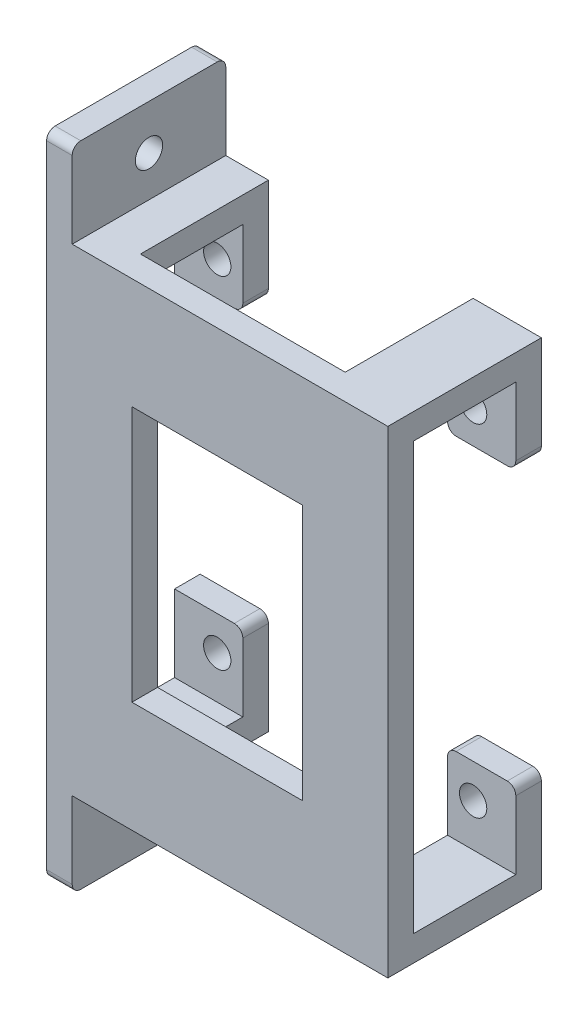
SolidWorks part; units mm, degrees
ref_plane "前视基准面" through (0, 0, 0) normal (0, 0, 1) x (1, 0, 0)
ref_plane "上视基准面" through (0, 0, 0) normal (0, 1, 0) x (1, 0, 0)
ref_plane "右视基准面" through (0, 0, 0) normal (1, 0, 0) x (0, 0, -1)
sketch "草图1" plane through (0, 0, 0) normal (0, 0, 1) x (1, 0, 0)
  line L1 (-15, -20) -> (15, -20) construction
  line L2 (-15, -20) -> (-15, 20) construction
  line L3 (-15, 20) -> (15, 20) construction
  line L4 (15, -20) -> (15, 20) construction
  line L5 (-15, -20) -> (15, 20) construction
  line L6 (-15, 20) -> (15, -20) construction
  line L7 (-20, -25) -> (20, -25)
  line L8 (-20, -25) -> (-20, 25)
  line L9 (-20, 25) -> (20, 25)
  line L10 (20, -25) -> (20, 25)
  line L11 (-20, -25) -> (20, 25) construction
  line L12 (-20, 25) -> (20, -25) construction
  circle A0 centre (-15, 20) radius 1.6
  circle A1 centre (15, 20) radius 1.6
  circle A2 centre (15, -20) radius 1.6
  circle A3 centre (-15, -20) radius 1.6
  point P0 (0, 0)
  point P5 (0, 0)
  dimension "D5" = 3.2
  dimension "D1" = 40
  dimension "D2" = 30
  dimension "D3" = 5
  dimension "D4" = 5
extrude "凸台-拉伸1" add sketch "草图1" along normal blind 3
sketch "草图2" plane through (0, 0, 0) normal (0, 0, -1) x (-1, 0, 0)
  line L1 (-20, 25) -> (-12, 25)
  line L2 (-20, 25) -> (-20, 28)
  line L3 (-20, 28) -> (-12, 28)
  line L4 (-12, 25) -> (-12, 28)
  line L5 (20, 25) -> (12, 25)
  line L6 (20, 25) -> (20, 28)
  line L7 (20, 28) -> (12, 28)
  line L8 (12, 25) -> (12, 28)
  line L9 (-20, -25) -> (-12, -25)
  line L10 (-20, -25) -> (-20, -28)
  line L11 (-20, -28) -> (-12, -28)
  line L12 (-12, -25) -> (-12, -28)
  line L13 (20, -25) -> (12, -25)
  line L14 (20, -25) -> (20, -28)
  line L15 (20, -28) -> (12, -28)
  line L16 (12, -25) -> (12, -28)
  dimension "D1" = 3
  dimension "D2" = 3
  dimension "D3" = 8
extrude "凸台-拉伸2" add sketch "草图2" against normal blind 15
sketch "草图3" plane through (0, 0, 15) normal (0, 0, 1) x (1, 0, 0)
  line L1 (-20, 28) -> (20, 28)
  line L2 (-20, 28) -> (-20, -28)
  line L3 (-20, -28) -> (20, -28)
  line L4 (20, 28) -> (20, -28)
  line L5 (20, -28) -> (12, -28) construction
extrude "凸台-拉伸3" add sketch "草图3" along normal blind 3
sketch "草图4" plane through (0, 0, 0) normal (0, 0, -1) x (-1, 0, 0)
  line L0 (20, 28) -> (20, -28) construction
  line L1 (-20, -16) -> (20, -16)
  line L2 (-20, -16) -> (-20, 16)
  line L3 (-20, 16) -> (20, 16)
  line L4 (20, -16) -> (20, 16)
  line L5 (-20, -16) -> (20, 16) construction
  line L6 (-20, 16) -> (20, -16) construction
  circle A0 centre (15, 20) radius 1.6 construction
  point P0 (0, 0)
  dimension "D1" = 4
extrude "切除-拉伸1" cut sketch "草图4" against normal up to next
sketch "草图5" plane through (0, 0, 0) normal (0, 0, -1) x (-1, 0, 0)
  line L1 (-12, 25) -> (12, 25)
  line L2 (-12, 25) -> (-12, -25)
  line L3 (-12, -25) -> (12, -25)
  line L4 (12, 25) -> (12, -25)
extrude "切除-拉伸2" cut sketch "草图5" against normal up to next
fillet "圆角1" radius 1 6 edges at (20, -16, 1.5) (12, -16, 1.5) (-12, -16, 1.5) (-12, 16, 1.5) (12, 16, 1.5) (20, 16, 1.5)
sketch "草图10" plane through (0, 0, 15) normal (0, 0, -1) x (-1, 0, 0)
  line L1 (-10, -15) -> (10, -15)
  line L2 (-10, -15) -> (-10, 15)
  line L3 (-10, 15) -> (10, 15)
  line L4 (10, -15) -> (10, 15)
  line L5 (-10, -15) -> (10, 15) construction
  line L6 (-10, 15) -> (10, -15) construction
  point P0 (0, 0)
  dimension "D1" = 30
  dimension "D2" = 20
extrude "切除-拉伸4" cut sketch "草图10" against normal up to next
sketch "草图11" plane through (0, 28, 0) normal (0, 1, 0) x (1, 0, 0)
  line L0 (20, -18) -> (-20, -18) construction
  line L1 (-20, 0) -> (-17, 0)
  line L2 (-20, 0) -> (-20, -18)
  line L3 (-20, -18) -> (-17, -18)
  line L4 (-17, 0) -> (-17, -18)
  dimension "D1" = 3
extrude "凸台-拉伸4" add sketch "草图11" along normal blind 10
mirror "镜向1" about plane through (0, 0, 0) normal (0, 1, 0) of "凸台-拉伸4"
sketch "草图12" plane through (-17, 0, 0) normal (1, 0, 0) x (0, 0, -1)
  line L0 (-9, 38) -> (-9, -38) construction
  line L1 (-18, 38) -> (0, 38) construction
  line L2 (-18, -38) -> (0, -38) construction
  line L3 (0, 0) -> (-22.6467, 0) construction
  circle A0 centre (-9, 32.75) radius 1.6
  circle A1 centre (-9, -32.75) radius 1.6
  dimension "D1" = 65.5
  dimension "D2" = 3.2
extrude "切除-拉伸5" cut sketch "草图12" against normal up to next
fillet "圆角2" radius 1 4 edges at (-18.5, 38, 18) (-18.5, 38, 0) (-18.5, -38, 0) (-18.5, -38, 18)
